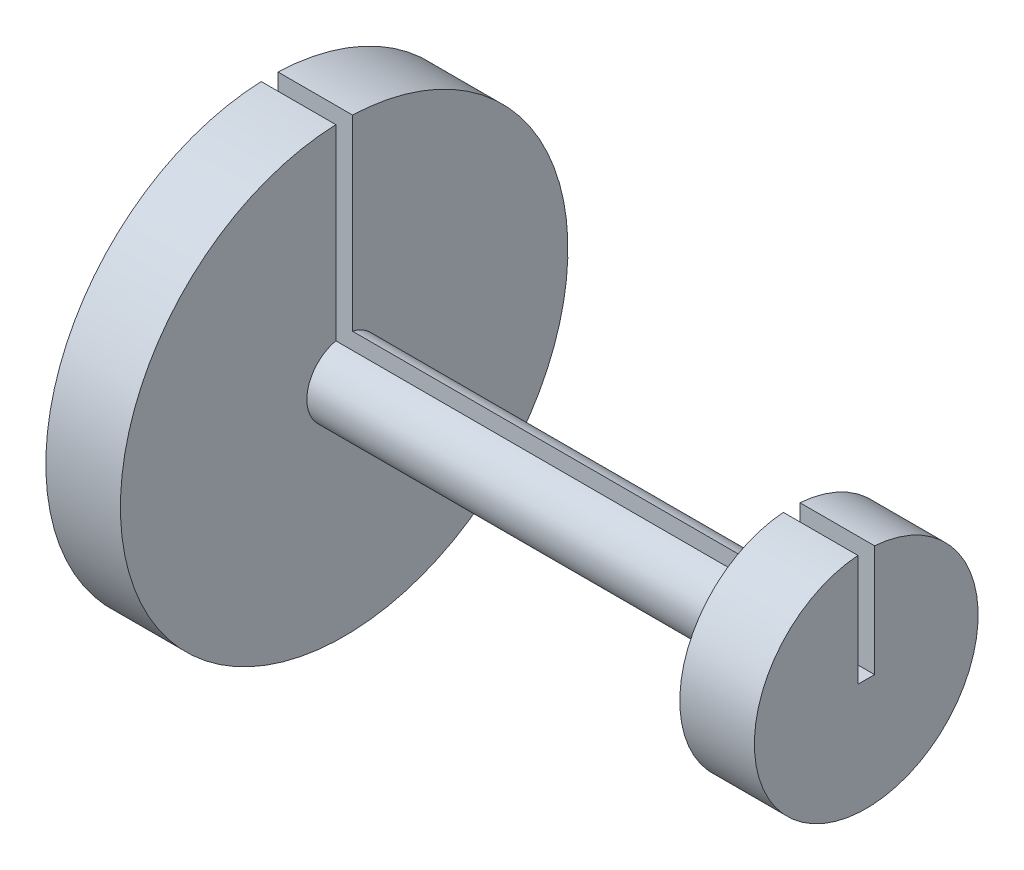
SolidWorks part; units mm, degrees
ref_plane "Front Plane" through (0, 0, 0) normal (0, 0, 1) x (1, 0, 0)
ref_plane "Top Plane" through (0, 0, 0) normal (0, 1, 0) x (1, 0, 0)
ref_plane "Right Plane" through (0, 0, 0) normal (1, 0, 0) x (0, 0, -1)
sketch "Sketch1" plane through (0, 0, 0) normal (0, 0, 1) x (1, 0, 0)
  line L0 (0, 0) -> (0, 30)
  line L1 (0, 30) -> (10, 30)
  line L2 (10, 30) -> (10, 5)
  line L3 (10, 5) -> (70, 5)
  line L4 (70, 5) -> (70, 15)
  line L5 (70, 15) -> (80, 15)
  line L6 (80, 15) -> (80, 0)
  line L7 (80, 0) -> (0, 0) construction
  line L8 (0, 0) -> (80, 0)
  dimension "D1" = 5
  dimension "D2" = 60
  dimension "D3" = 10
  dimension "D4" = 10
  dimension "D5" = 60
  dimension "D6" = 30
revolve "Revolve1" add sketch "Sketch1" angle 360 about L7
sketch "Sketch2" plane through (80, 0, 0) normal (1, 0, 0) x (0, 0, -1)
  line L1 (-1.1166, 0) -> (1.1166, 0)
  line L2 (-1.1166, 0) -> (-1.1166, 31.6073)
  line L3 (-1.1166, 31.6073) -> (1.1166, 31.6073)
  line L4 (1.1166, 0) -> (1.1166, 31.6073)
  point P4 (-5.1104, -0.0859)
  point P5 (0, 0)
  dimension "D1" = 31.6073
  dimension "D2" = 2.2331
extrude "Cut-Extrude1" cut sketch "Sketch2" against normal up to vertex (80 mm away) up to point (0, 0, 0)
